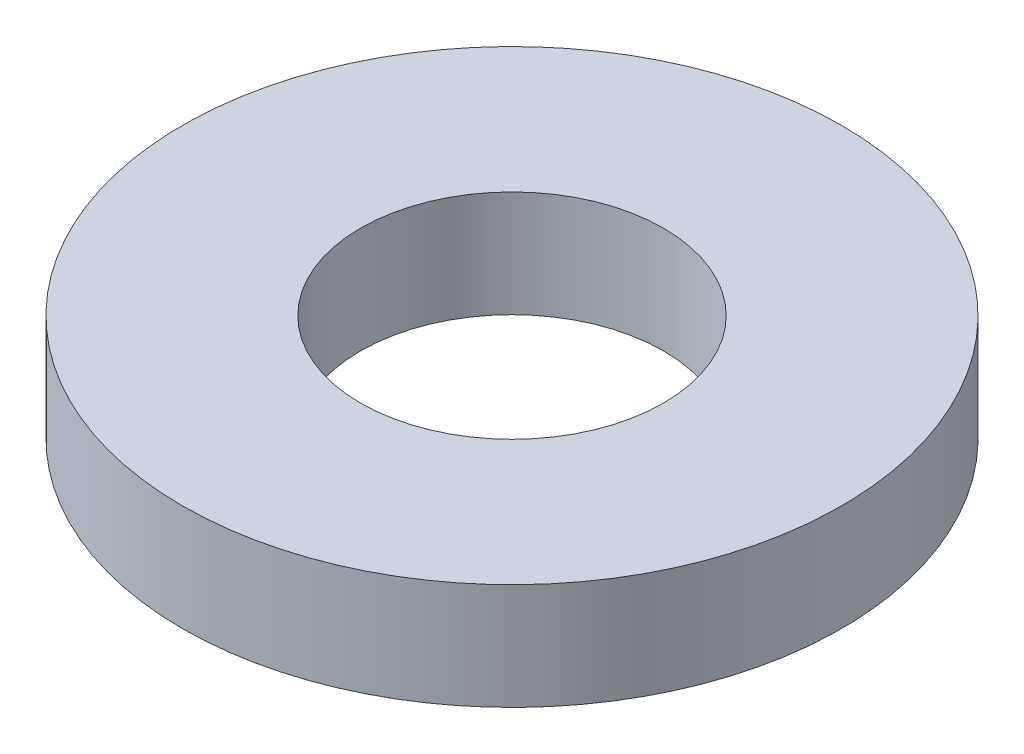
SolidWorks part; units mm, degrees
ref_plane "Front Plane" through (0, 0, 0) normal (0, 0, 1) x (1, 0, 0)
ref_plane "Top Plane" through (0, 0, 0) normal (0, 1, 0) x (1, 0, 0)
ref_plane "Right Plane" through (0, 0, 0) normal (1, 0, 0) x (0, 0, -1)
sketch "Sketch1" plane through (0, 0, 0) normal (0, 1, 0) x (1, 0, 0)
  circle A0 centre (0, 0) radius 1.425
  circle A1 centre (0, 0) radius 3.1
  dimension "D1" = 6.2
  dimension "D2" = 2.85
extrude "Boss-Extrude1" add sketch "Sketch1" along normal blind 1
equation "\"ID\" = 2.85mm"
equation "\"D2@Sketch1\"=\"ID\""
equation "\"Height\"= 1"
equation "\"D1@Boss-Extrude1\"=\"Height\""
